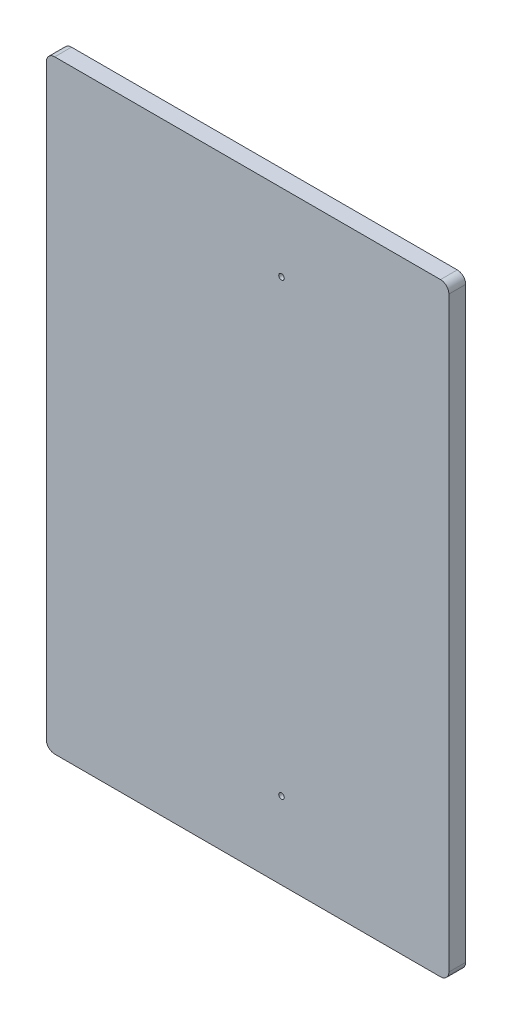
SolidWorks part; units mm, degrees
ref_plane "Front Plane" through (0, 0, 0) normal (0, 0, 1) x (1, 0, 0)
ref_plane "Top Plane" through (0, 0, 0) normal (0, 1, 0) x (1, 0, 0)
ref_plane "Right Plane" through (0, 0, 0) normal (1, 0, 0) x (0, 0, -1)
sketch "Sketch2" plane through (0, 0, 0) normal (0, 0, 1) x (1, 0, 0)
  line L0 (0, 19.05) -> (0, -438.15) construction
  line L1 (152.4, 19.05) -> (-152.4, 19.05)
  line L2 (152.4, 19.05) -> (152.4, -438.15)
  line L3 (152.4, -438.15) -> (-152.4, -438.15)
  line L4 (-152.4, 19.05) -> (-152.4, -438.15)
  line L7 (0, -419.1) -> (0, 0) construction
  line L8 (152.4, -209.55) -> (-152.4, -209.55) construction
  dimension "D1" = 304.8
  dimension "D2" = 457.2
extrude "Boss-Extrude1" add sketch "Sketch2" along normal blind 12.7
fillet "Fillet1" radius 6.35 4 edges at (152.4, 19.05, 6.35) (152.4, -438.15, 6.35) (-152.4, -438.15, 6.35) (-152.4, 19.05, 6.35)
sketch "Sketch4" plane through (0, 0, 0) normal (0, 0, -1) x (-1, 0, 0)
  line L0 (-152.4, -209.55) -> (152.4, -209.55) construction
  line L1 (-152.4, 19.05) -> (-152.4, -438.15) construction
  circle A0 centre (-25.654, -39.37) radius 2.0955
  circle A1 centre (-25.654, -379.73) radius 2.0955
  dimension "D1" = 4.191
extrude "Cut-Extrude1" cut sketch "Sketch4" against normal through all
